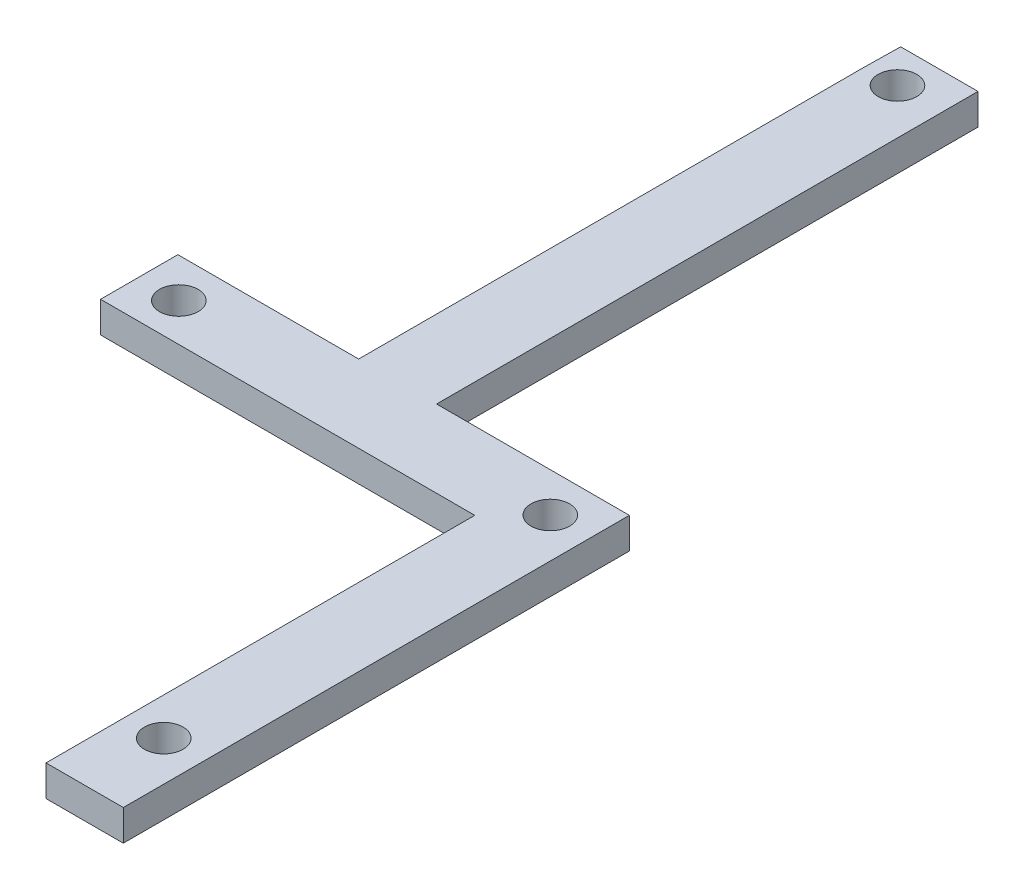
SolidWorks part; units mm, degrees
ref_plane "Alzado" through (0, 0, 0) normal (0, 0, 1) x (1, 0, 0)
ref_plane "Planta" through (0, 0, 0) normal (0, 1, 0) x (1, 0, 0)
ref_plane "Vista lateral" through (0, 0, 0) normal (1, 0, 0) x (0, 0, -1)
sketch "Croquis1" plane through (0, 0, 0) normal (0, 1, 0) x (1, 0, 0)
  line L0 (15.056, 39.7048) -> (15.056, 26.1682)
  line L1 (15.056, 26.1682) -> (15.056, 7.0743)
  line L2 (15.056, 7.0743) -> (3.3625, 7.0743)
  line L3 (3.3625, 7.0743) -> (3.3625, 2.0743)
  line L4 (3.3625, 2.0743) -> (27.5654, 2.0743)
  line L5 (27.5654, 2.0743) -> (27.5654, -25.6573)
  line L6 (27.5654, -25.6573) -> (32.5654, -25.6573)
  line L7 (32.5654, -25.6573) -> (32.5654, 7.0743)
  line L8 (32.5654, 7.0743) -> (20.0948, 7.0743)
  line L9 (20.0948, 7.0743) -> (20.0948, 42.0922)
  line L10 (20.0948, 42.0922) -> (15.0948, 42.0922)
  line L11 (15.0948, 42.0922) -> (15.056, 39.7048)
  circle A3 centre (17.1587, 39.8198) radius 1.25
  point P12 (15.056, 7.0742)
  point P13 (28.315, 2.1308)
  point P14 (3.3625, 7.0743)
  point P24 (0, 0)
  dimension "D1" = 5
  dimension "D2" = 5
  dimension "D3" = 5
extrude "Saliente-Extruir2" add sketch "Croquis1" along normal blind 2 contours L5 L6 L7 L8 L9 L10 L11 L0 L1 L2 L3 L4
sketch "Croquis2" plane through (0, 2, 0) normal (0, 1, 0) x (1, 0, 0)
  circle A0 centre (17.1587, 39.8198) radius 1.25
  circle A1 centre (5.9623, 4.5358) radius 1.25
  circle A2 centre (29.9887, 4.5358) radius 1.25
  circle A3 centre (29.9887, -20.4663) radius 1.25
  point P8 (5.6113, 3.9667)
  point P9 (4.7844, 4.2491)
  point P10 (29.0153, 4.2517)
  point P12 (29.0153, -20.7977)
  point P13 (29.0153, 4.2491)
  point P14 (0, 0)
  point P15 (0, 0)
  point P16 (28.8978, 4.2491)
  point P17 (4.9862, 4.2491)
  point P18 (29.0153, 4.2517)
  point P20 (2.9226, 4.2517)
  point P21 (5.0163, 4.2517)
  point P23 (5.0163, 4.2517)
  point P24 (4.9247, 4.2517)
  point P25 (5.4211, 4.5358)
  point P26 (0, 0)
  point P27 (5.9623, 4.5358)
  point P28 (29.9887, -20.4663)
  dimension "D1" = 2.5
  dimension "D2" = 2.5
  dimension "D3" = 2.5
  dimension "D4" = 2.5
extrude "Cortar-Extruir1" cut sketch "Croquis2" against normal blind 2
